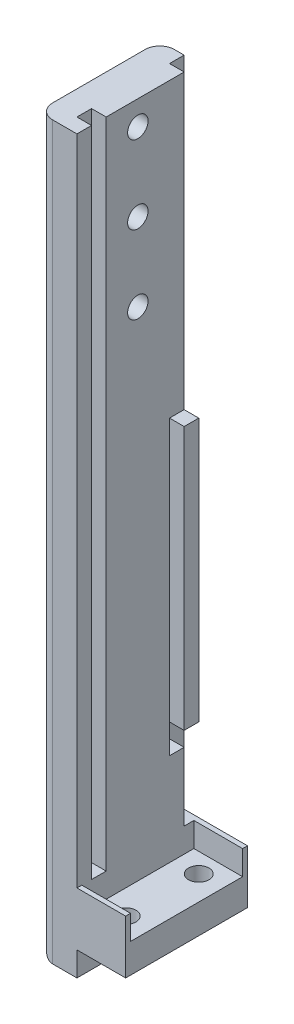
SolidWorks part; units mm, degrees
material "ABS"
ref_plane "前基準面" through (0, 0, 0) normal (0, 0, 1) x (1, 0, 0)
ref_plane "上基準面" through (0, 0, 0) normal (0, 1, 0) x (1, 0, 0)
ref_plane "右基準面" through (0, 0, 0) normal (1, 0, 0) x (0, 0, -1)
sketch "草圖1" plane through (0, 0, 0) normal (0, 0, 1) x (1, 0, 0)
  line L0 (-18, 116.9353) -> (-10, 116.9353)
  line L1 (-10, 116.9353) -> (-10, -22.0647)
  line L2 (-10, -22.0647) -> (0, -22.0647)
  line L3 (0, -22.0647) -> (0, -28.0647)
  line L4 (0, -28.0647) -> (-10, -28.0647)
  line L5 (-10, -28.0647) -> (-10, -33.0647)
  line L6 (-10, -33.0647) -> (-18, -33.0647)
  line L7 (-18, -33.0647) -> (-18, 116.9353)
  dimension "D1" = 10
  dimension "D2" = 10
  dimension "D3" = 6
  dimension "D4" = 8
  dimension "D5" = 150
  dimension "D6" = 5
extrude "填料-伸長1" add sketch "草圖1" along normal blind 25
sketch "草圖2" plane through (0, -22.0647, 0) normal (0, 1, 0) x (1, 0, 0)
  line L0 (0, -25) -> (0, 0) construction
  line L1 (0, 0) -> (-10, 0) construction
  circle A0 centre (-5, -5) radius 2.1
  circle A1 centre (-5, -20) radius 2.1
  dimension "D1" = 5
  dimension "D2" = 5
  dimension "D3" = 4.2
  dimension "D4" = 2
extrude "除料-伸長1" cut sketch "草圖2" against normal blind 25
sketch "草圖3" plane through (-18, 0, 0) normal (-1, 0, 0) x (0, 0, 1)
  line L0 (25, 116.9353) -> (0, 116.9353) construction
  line L1 (25, 116.9353) -> (25, -33.0647) construction
  circle A0 centre (12.5, 111.9353) radius 2.1
  circle A1 centre (12.5, 95.9353) radius 2.1
  circle A2 centre (12.5, 79.9353) radius 2.1
  point P4 (12.5, 116.9353)
  dimension "D1" = 4.2
  dimension "D2" = 5
  dimension "D3" = 12.5
  dimension "D4" = 3
extrude "除料-伸長2" cut sketch "草圖3" against normal blind 25
sketch "草圖4" plane through (0, -22.0647, 0) normal (0, 1, 0) x (1, 0, 0)
  line L0 (-10, -25) -> (-10, 0) construction
  line L1 (0, 0) -> (-10, 0)
  line L2 (0, 0) -> (0, -1)
  line L3 (0, -1) -> (-10, -1)
  line L4 (-10, 0) -> (-10, -1)
  line L6 (0, -25) -> (-10, -25)
  line L7 (0, -25) -> (0, -24)
  line L8 (0, -24) -> (-10, -24)
  line L9 (-10, -25) -> (-10, -24)
  dimension "D1" = 1
  dimension "D2" = 1
extrude "填料-伸長2" add sketch "草圖4" along normal blind 5
sketch "草圖5" plane through (0, 116.9353, 0) normal (0, 1, 0) x (1, 0, 0)
  line L0 (-10, -25) -> (-10, 0) construction
  line L5 (-10, -25) -> (-18, -25) construction
  line L6 (-10, -22) -> (-13, -22)
  line L7 (-10, -22) -> (-10, -19)
  line L8 (-10, -19) -> (-13, -19)
  line L9 (-13, -22) -> (-13, -19)
  dimension "D1" = 3
  dimension "D2" = 3
  dimension "D3" = 3
extrude "除料-伸長3" cut sketch "草圖5" against normal up to surface (134 mm away) up to face at (-5, -17.0647, 24.5)
fillet "圓角1" radius 3 3 edges at (-18, -33.0647, 12.5) (-18, 41.9353, 25) (-18, 41.9353, 0)
sketch "草圖8" plane through (-18, 0, 0) normal (-1, 0, 0) x (0, 0, 1)
  text T0 "\r\nright down side           \r\n" font "Comic Sans MS" height in points 26
extrude "除料-伸長8" cut sketch "草圖8" against normal blind 2
sketch "草圖9" plane through (0, 116.9353, 0) normal (0, 1, 0) x (1, 0, 0)
  line L1 (-10, 0) -> (-13, 0)
  line L2 (-10, 0) -> (-10, -3)
  line L3 (-10, -3) -> (-13, -3)
  line L4 (-13, 0) -> (-13, -3)
  dimension "D1" = 3
  dimension "D2" = 3
extrude "除料-伸長9" cut sketch "草圖9" against normal blind 60
sketch "草圖10" plane through (-10, 0, 0) normal (1, 0, 0) x (0, 0, -1)
  line L0 (0, -17.0647) -> (0, 56.9353) construction
  line L1 (-3, 56.9353) -> (-6, 56.9353)
  line L2 (-3, 56.9353) -> (-3, -3.0647)
  line L3 (-3, -3.0647) -> (-6, -3.0647)
  line L4 (-6, 56.9353) -> (-6, -3.0647)
  line L5 (-3, -3.0647) -> (0, -3.0647)
  line L6 (-3, -3.0647) -> (-3, -17.0647)
  line L7 (-3, -17.0647) -> (0, -17.0647)
  line L8 (0, -3.0647) -> (0, -17.0647)
  line L10 (-3, 56.9353) -> (0, 56.9353)
  line L11 (-3, 56.9353) -> (-3, 53.9353)
  line L12 (-3, 53.9353) -> (0, 53.9353)
  line L13 (0, 56.9353) -> (0, 53.9353)
  line L14 (-3, -3.0647) -> (0, -3.0647)
  line L15 (-3, -3.0647) -> (-3, -0.0647)
  line L16 (-3, -0.0647) -> (0, -0.0647)
  line L17 (0, -3.0647) -> (0, -0.0647)
  point P15 (0, 0)
  line M9 (0, 56.9353) -> (-3, 56.9353)
  line M21 (-1, -17.0647) -> (0, -17.0647)
  line M22 (0, -17.0647) -> (0, 56.9353)
  dimension "D1" = 60
  dimension "D2" = 3
  dimension "D3" = 3
  dimension "D4" = 3
extrude "除料-伸長10" cut sketch "草圖10" against normal blind 3 contours L1 L4 L3 L2 | L2 L12 M22 M9 | L16 L2 L5 M22 | L6 L7 L5 M21 M22
